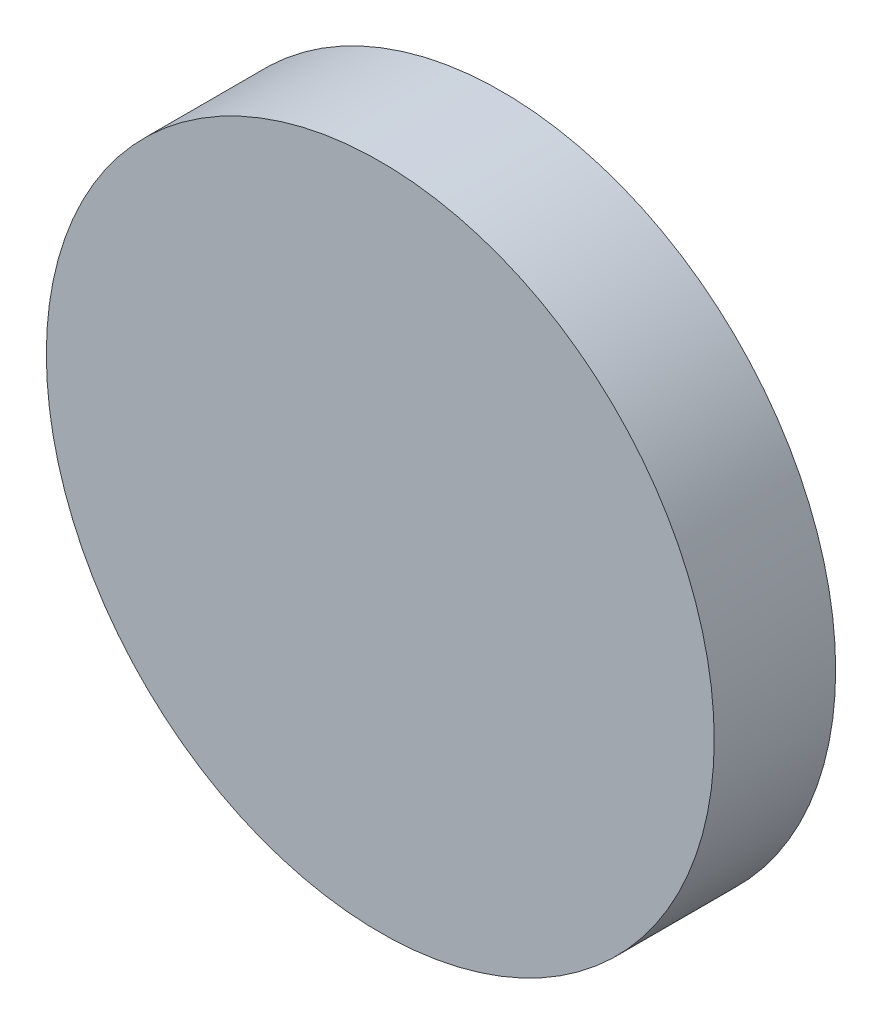
SolidWorks part; units mm, degrees
ref_plane "Front Plane" through (0, 0, 0) normal (0, 0, 1) x (1, 0, 0)
ref_plane "Top Plane" through (0, 0, 0) normal (0, 1, 0) x (1, 0, 0)
ref_plane "Right Plane" through (0, 0, 0) normal (1, 0, 0) x (0, 0, -1)
sketch "Sketch1" plane through (0, 0, 0) normal (0, 0, 1) x (1, 0, 0)
  circle A0 centre (0, 0) radius 34.925
extrude "Boss-Extrude1" add sketch "Sketch1" along normal blind 12.7
